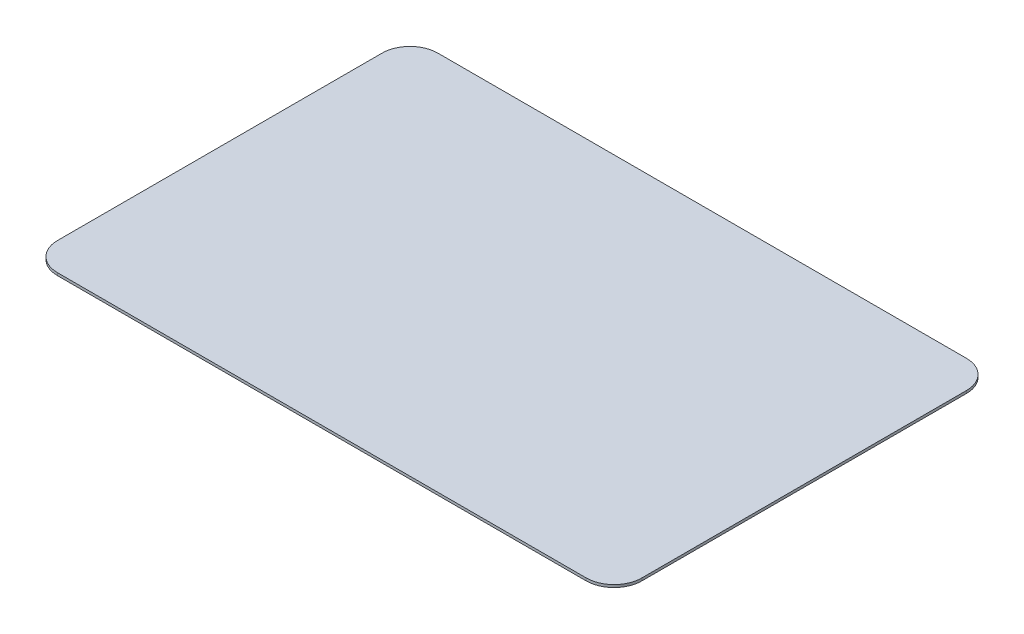
SolidWorks part; units mm, degrees
ref_plane "Front" through (0, 0, 0) normal (0, 0, 1) x (1, 0, 0)
ref_plane "Top" through (0, 0, 0) normal (0, 1, 0) x (1, 0, 0)
ref_plane "Right" through (0, 0, 0) normal (1, 0, 0) x (0, 0, -1)
sketch "Эскиз1" plane through (0, 0, 0) normal (0, 1, 0) x (1, 0, 0)
  line L1 (3, 0) -> (60, 0)
  line L2 (0, -3) -> (0, -38)
  line L3 (3, -41) -> (60, -41)
  line L4 (63, -3) -> (63, -38)
  arc A0 (60, 0) -> (63, -3) centre (60, -3) cw
  arc A1 (60, -41) -> (63, -38) centre (60, -38) ccw
  arc A2 (0, -38) -> (3, -41) centre (3, -38) ccw
  arc A3 (3, 0) -> (0, -3) centre (3, -3) ccw
  point P7 (63, 0)
  point P12 (0, -41)
  point P15 (0, 0)
  dimension "D3" = 3
  dimension "D1" = 63
  dimension "D2" = 41
extrude "Бобышка-Вытянуть1" add sketch "Эскиз1" along normal blind 0.28
